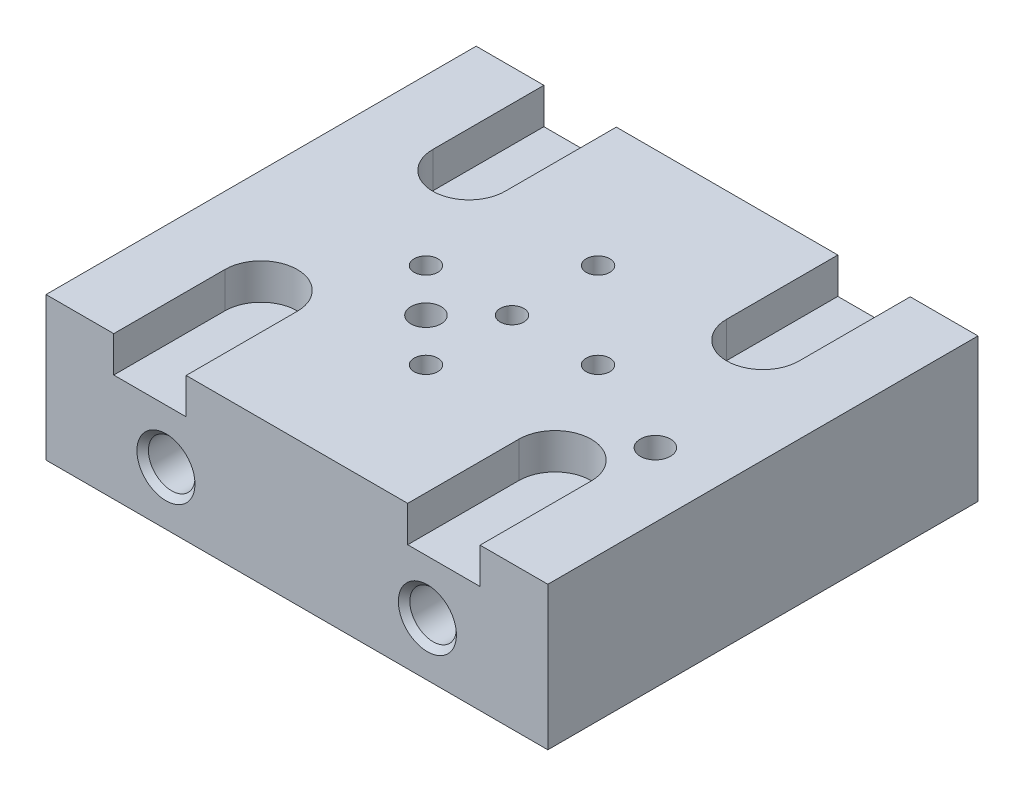
SolidWorks part; units mm, degrees
ref_plane "Front Plane" through (0, 0, 0) normal (0, 0, 1) x (1, 0, 0)
ref_plane "Top Plane" through (0, 0, 0) normal (0, 1, 0) x (1, 0, 0)
ref_plane "Right Plane" through (0, 0, 0) normal (1, 0, 0) x (0, 0, -1)
sketch "Sketch3" plane through (0, 0, 0) normal (0, 1, 0) x (1, 0, 0)
  line L1 (0, 0) -> (70, 0)
  line L2 (0, 0) -> (0, -60)
  line L3 (0, -60) -> (70, -60)
  line L4 (70, 0) -> (70, -60)
  dimension "D1" = 70
  dimension "D2" = 60
extrude "Boss-Extrude3" add sketch "Sketch3" along normal blind 20
sketch "Sketch4" plane through (0, 20, 0) normal (0, 1, 0) x (1, 0, 0)
  line L0 (35, 0) -> (35, -60) construction
  line L1 (70, 0) -> (0, 0) construction
  line L2 (0, -60) -> (70, -60) construction
  line L3 (0, -30) -> (70, -30) construction
  line L4 (0, 0) -> (0, -60) construction
  line L5 (70, -60) -> (70, 0) construction
  line L6 (21.35, -30) -> (21.35, 0) construction
  line L7 (0, 0) -> (70, 0) construction
  line L8 (24.65, -30) -> (24.65, 0) construction
  line L9 (45.35, -30) -> (45.35, 0) construction
  line L10 (48.65, -30) -> (48.65, 0) construction
  circle A0 centre (35, -30) radius 1.65
  circle A1 centre (35, -18) radius 1.65
  circle A2 centre (47, -30) radius 1.65
  circle A3 centre (35, -42) radius 1.65
  circle A4 centre (23, -30) radius 1.65
  dimension "D1" = 3.3
  dimension "D2" = 12
  dimension "D3" = 12
  dimension "D4" = 12
  dimension "D5" = 12
extrude "Cut-Extrude1" cut sketch "Sketch4" against normal through all
sketch "Sketch6" plane through (0, 0, 0) normal (0, -1, 0) x (1, 0, 0)
  line L0 (70, 30) -> (0, 30) construction
  line L1 (55, 24) -> (35, 24) construction
  line L2 (67, 24) -> (70, 24) construction
  line L3 (70, 60) -> (70, 0) construction
  line L4 (0, 0) -> (0, 60) construction
  line L5 (29, 24) -> (29, 0) construction
  line L6 (70, 0) -> (0, 0) construction
  line L7 (61, 24) -> (61, 0) construction
  line L8 (35, 24) -> (35, 0) construction
  line L9 (55, 24) -> (55, 0) construction
  line L10 (23, 24) -> (23, 0) construction
  line L11 (67, 24) -> (67, 0) construction
  line L12 (58.9, 24) -> (58.9, 0) construction
  line L13 (63.1, 24) -> (63.1, 0) construction
  line L14 (31.1, 24) -> (31.1, 0) construction
  line L15 (26.9, 24) -> (26.9, 0) construction
  line L16 (35, 0) -> (35, 60) construction
  line L17 (34.9322, 16.3514) -> (34.9322, 0) construction
  line L18 (34.9322, 43.6486) -> (34.9322, 60) construction
  line L19 (26.9, 36) -> (26.9, 60) construction
  line L20 (31.1, 36) -> (31.1, 60) construction
  line L21 (63.1, 36) -> (63.1, 60) construction
  line L22 (58.9, 36) -> (58.9, 60) construction
  line L23 (67, 36) -> (67, 60) construction
  line L24 (23, 36) -> (23, 60) construction
  line L25 (55, 36) -> (55, 60) construction
  line L26 (35, 36) -> (35, 60) construction
  line L27 (61, 36) -> (61, 60) construction
  line L28 (29, 36) -> (29, 60) construction
  line L29 (67, 36) -> (70, 36) construction
  line L30 (55, 36) -> (35, 36) construction
  circle A2 centre (61, 24) radius 6 construction
  circle A3 centre (29, 24) radius 6 construction
  circle A4 centre (61, 24) radius 2.1
  circle A5 centre (29, 24) radius 2.1
  circle A6 centre (35, 18) radius 1.65 construction
  circle A7 centre (29, 36) radius 6 construction
  circle A8 centre (61, 36) radius 6 construction
  circle A9 centre (29, 36) radius 2.1
  circle A10 centre (61, 36) radius 2.1
  dimension "D1" = 12
  dimension "D2" = 20
  dimension "D3" = 4.2
extrude "Cut-Extrude2" cut sketch "Sketch6" against normal through all contours A9 | A10 | A5
sketch "Sketch9" plane through (0, 0, 60) normal (0, 0, -1) x (-1, 0, 0)
  line L0 (-29, 0) -> (-29, 20) construction
  line L1 (-70, 20) -> (0, 20) construction
  line L2 (-61, 0) -> (-61, 20) construction
  line L3 (-67, 0) -> (-55, 0) construction
  line L4 (-23, 0) -> (-23, 20) construction
  line L5 (-35, 0) -> (-35, 20) construction
  line L6 (-55, 0) -> (-55, 20) construction
  line L7 (-67, 0) -> (-67, 20) construction
  line L8 (-58.9, 0) -> (-58.9, 20) construction
  line L9 (-63.1, 0) -> (-63.1, 20) construction
  line L10 (-31.1, 0) -> (-31.1, 20) construction
  line L11 (-26.9, 0) -> (-26.9, 20) construction
  line L12 (-58.9, 7.5) -> (-56.45, 7.5) construction
  line L13 (-53.2, 10.75) -> (-53.2, 20) construction
  line L14 (-13.4822, 7.5) -> (0, 7.5) construction
  line L15 (-19.9822, 7.5) -> (-21.35, 7.5) construction
  line L16 (-16.7322, 20) -> (-16.7322, 10.75) construction
  line L17 (0, 20) -> (0, 0) construction
  line L18 (-34.9322, 0) -> (-34.9322, 20) construction
  line L19 (-34.9322, 0) -> (-34.9322, 20) construction
  line L20 (-49.95, 7.5) -> (-34.9322, 7.5) construction
  line L21 (-21.35, 20) -> (-21.35, 0) construction
  line L22 (0, 0) -> (-70, 0) construction
  line L23 (-24.65, 20) -> (-24.65, 0) construction
  line L24 (-45.35, 20) -> (-45.35, 0) construction
  line L25 (-48.65, 20) -> (-48.65, 0) construction
  line L26 (0, 7.5) -> (0, 20) construction
  circle A0 centre (-53.2, 7.5) radius 3.25
  circle A1 centre (-16.7322, 7.5) radius 3.25
  dimension "D1" = 6.5
  dimension "D2" = 18.2
  dimension "D3" = 18.2
  dimension "D4" = 12.5
extrude "Cut-Extrude3" cut sketch "Sketch9" along normal blind 40.25
sketch "Sketch11" plane through (0, 0, 0) normal (0, -1, 0) x (1, 0, 0)
  line L0 (70, 30) -> (0, 30) construction
  circle A0 centre (23, 30) radius 3
  circle A1 centre (35, 42) radius 3
  circle A2 centre (35, 30) radius 3
  circle A3 centre (35, 18) radius 3
  circle A4 centre (47, 30) radius 3
  circle M3 centre (35, 18) radius 1.65
  circle M4 centre (47, 30) radius 1.65
  circle M5 centre (35, 42) radius 1.65
  circle M6 centre (23, 30) radius 1.65
  circle M7 centre (35, 30) radius 1.65
  dimension "D1" = 6
extrude "Cut-Extrude4" cut sketch "Sketch11" against normal blind 3 contours A3 M3 | A2 M7 | A4 M4 | A0 M6 | A1 M5 | M5 | M6 | M7 | M4 | M3
sketch "Sketch12" plane through (0, 20, 0) normal (0, 1, 0) x (1, 0, 0)
  line L0 (35, -60.1049) -> (14.5, -60.1049) construction
  line L1 (35, 0.1049) -> (35, -60.1049) construction
  line L2 (14.5, -60.1049) -> (14.5, -44.5) construction
  line L3 (9.45, -60.1049) -> (9.45, -44.5)
  line L4 (19.55, -60.1049) -> (19.55, -44.5)
  line L5 (70, -30) -> (0, -30) construction
  line L6 (35, 0) -> (35, -60) construction
  line L7 (35, 0.1049) -> (14.5, 0.1049) construction
  line L8 (55.5, -60.1049) -> (55.5, -44.5) construction
  line L9 (60.55, -60.1049) -> (60.55, -44.5)
  line L10 (50.45, -60.1049) -> (50.45, -44.5)
  line L11 (55.5, 0.1049) -> (55.5, -15.5) construction
  line L12 (60.55, 0.1049) -> (60.55, -15.5)
  line L13 (50.45, 0.1049) -> (50.45, -15.5)
  line L14 (14.5, 0.1049) -> (14.5, -15.5) construction
  line L15 (9.45, 0.1049) -> (9.45, -15.5)
  line L16 (19.55, 0.1049) -> (19.55, -15.5)
  arc A0 (9.45, -60.1049) -> (19.55, -60.1049) centre (14.5, -60.1049) ccw
  arc A1 (19.55, -44.5) -> (9.45, -44.5) centre (14.5, -44.5) ccw
  arc A3 (60.55, -60.1049) -> (50.45, -60.1049) centre (55.5, -60.1049) cw
  arc A4 (50.45, -44.5) -> (60.55, -44.5) centre (55.5, -44.5) cw
  arc A6 (60.55, 0.1049) -> (50.45, 0.1049) centre (55.5, 0.1049) ccw
  arc A7 (50.45, -15.5) -> (60.55, -15.5) centre (55.5, -15.5) ccw
  arc A8 (9.45, 0.1049) -> (19.55, 0.1049) centre (14.5, 0.1049) cw
  arc A9 (19.55, -15.5) -> (9.45, -15.5) centre (14.5, -15.5) cw
  point P0 (14.5, -52.3025)
  point P19 (35, -30)
  point P23 (55.5, -52.3025)
  point P29 (55.5, -7.6975)
  point P36 (14.5, -7.6975)
  dimension "D4" = 5.05
  dimension "D1" = 20.5
extrude "Cut-Extrude5" cut sketch "Sketch12" against normal blind 5
chamfer "Chamfer1" distance 0.8 angle 45 2 edges at (13.4822, 7.5, 60) (49.95, 7.5, 60)
